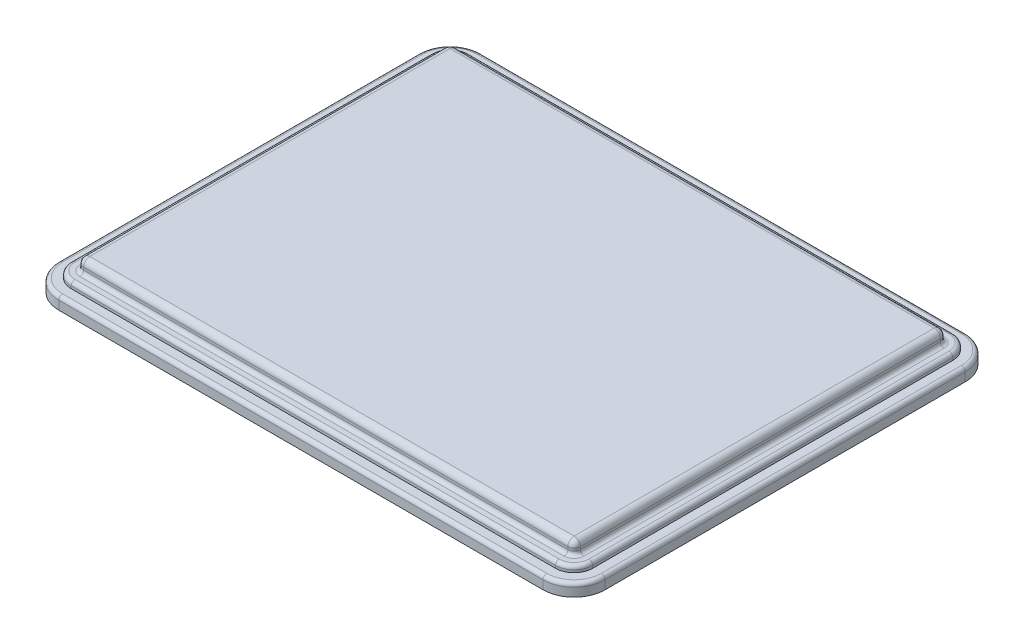
SolidWorks part; units mm, degrees
ref_plane "Front Plane" through (0, 0, 0) normal (0, 0, 1) x (1, 0, 0)
ref_plane "Top Plane" through (0, 0, 0) normal (0, 1, 0) x (1, 0, 0)
ref_plane "Right Plane" through (0, 0, 0) normal (1, 0, 0) x (0, 0, -1)
sketch "Sketch1" plane through (0, 0, 0) normal (0, 1, 0) x (1, 0, 0)
  line L1 (-200, 150) -> (200, 150)
  line L2 (-200, 150) -> (-200, -150)
  line L3 (-200, -150) -> (200, -150)
  line L4 (200, 150) -> (200, -150)
  line L5 (-200, 150) -> (200, -150) construction
  line L6 (-200, -150) -> (200, 150) construction
  point P0 (0, 0)
  dimension "D1" = 400
  dimension "D2" = 300
extrude "Boss-Extrude1" add sketch "Sketch1" along normal blind 10 contours L1 L4 L3 L2
fillet "Fillet1" radius 5 4 edges at (-200, 5, -150) (-200, 5, 150) (200, 5, -150) (200, 5, 150)
fillet "Fillet2" radius 5 8 edges at (198.5355, 10, -148.5355) (200, 10, 0) (198.5355, 10, 148.5355) (0, 10, 150) (-198.5355, 10, 148.5355) (-200, 10, 0) (-198.5355, 10, -148.5355) (0, 10, -150)
sketch "Sketch2" plane through (0, 0, 0) normal (0, -1, 0) x (1, 0, 0)
  line L0 (195, 160) -> (-195, 160)
  line L1 (-210, 145) -> (-210, -145)
  line L2 (-195, -160) -> (195, -160)
  line L3 (210, -145) -> (210, 145)
  line L4 (-200, 145) -> (-200, -145)
  line L5 (-195, -150) -> (195, -150)
  line L6 (200, -145) -> (200, 145)
  line L7 (195, 150) -> (-195, 150)
  line L8 (-200, 145) -> (-200, -145)
  line L9 (-195, -150) -> (195, -150)
  line L10 (200, -145) -> (200, 145)
  line L11 (195, 150) -> (-195, 150)
  arc A0 (-195, 160) -> (-210, 145) centre (-195, 145) ccw
  arc A1 (-210, -145) -> (-195, -160) centre (-195, -145) ccw
  arc A2 (195, -160) -> (210, -145) centre (195, -145) ccw
  arc A3 (210, 145) -> (195, 160) centre (195, 145) ccw
  arc A4 (-200, -145) -> (-195, -150) centre (-195, -145) ccw
  arc A5 (195, -150) -> (200, -145) centre (195, -145) ccw
  arc A6 (200, 145) -> (195, 150) centre (195, 145) ccw
  arc A7 (-195, 150) -> (-200, 145) centre (-195, 145) ccw
  arc A8 (-200, -145) -> (-195, -150) centre (-195, -145) ccw
  arc A9 (195, -150) -> (200, -145) centre (195, -145) ccw
  arc A10 (200, 145) -> (195, 150) centre (195, 145) ccw
  arc A11 (-195, 150) -> (-200, 145) centre (-195, 145) ccw
  dimension "D1" = 0
  dimension "D2" = 10
extrude "Boss-Extrude2" add sketch "Sketch2" along normal blind 5 contours L0 A0 L1 A1 L2 A2 L3 A3
sketch "Sketch3" plane through (0, -5, 0) normal (0, -1, 0) x (1, 0, 0)
  line L0 (195, 170) -> (-195, 170)
  line L1 (-220, 145) -> (-220, -145)
  line L2 (-195, -170) -> (195, -170)
  line L3 (220, -145) -> (220, 145)
  line L4 (195, 160) -> (-195, 160)
  line L5 (-210, 145) -> (-210, -145)
  line L6 (-195, -160) -> (195, -160)
  line L7 (210, -145) -> (210, 145)
  line L8 (195, 160) -> (-195, 160)
  line L9 (-210, 145) -> (-210, -145)
  line L10 (-195, -160) -> (195, -160)
  line L11 (210, -145) -> (210, 145)
  arc A0 (-195, 170) -> (-220, 145) centre (-195, 145) ccw
  arc A1 (-220, -145) -> (-195, -170) centre (-195, -145) ccw
  arc A2 (195, -170) -> (220, -145) centre (195, -145) ccw
  arc A3 (220, 145) -> (195, 170) centre (195, 145) ccw
  arc A4 (210, 145) -> (195, 160) centre (195, 145) ccw
  arc A5 (-195, 160) -> (-210, 145) centre (-195, 145) ccw
  arc A6 (-210, -145) -> (-195, -160) centre (-195, -145) ccw
  arc A7 (195, -160) -> (210, -145) centre (195, -145) ccw
  arc A8 (210, 145) -> (195, 160) centre (195, 145) ccw
  arc A9 (-195, 160) -> (-210, 145) centre (-195, 145) ccw
  arc A10 (-210, -145) -> (-195, -160) centre (-195, -145) ccw
  arc A11 (195, -160) -> (210, -145) centre (195, -145) ccw
  point P4 (0, 0)
  point P24 (-195, 160)
  point P26 (215, 145)
  point P27 (0, 0)
  dimension "D1" = 0
  dimension "D2" = 10
extrude "Boss-Extrude5" add sketch "Sketch3" along normal blind 10 separate body contours L1 A1 L2 A2 L3 A3 L0 A0
fillet "Fillet3" radius 3 16 edges at (-198.5355, 0, 148.5355) (0, 0, 150) (198.5355, 0, 148.5355) (200, 0, 0) (198.5355, 0, -148.5355) (0, 0, -150) (-198.5355, 0, -148.5355) (-200, 0, 0) (0, 0, 160) (-205.6066, 0, 155.6066) (-210, 0, 0) (-205.6066, 0, -155.6066) (0, 0, -160) (205.6066, 0, -155.6066) (210, 0, 0) (205.6066, 0, 155.6066)
fillet "Fillet4" radius 3 8 edges at (-220, -5, 0) (-212.6777, -5, -162.6777) (0, -5, -170) (212.6777, -5, -162.6777) (220, -5, 0) (212.6777, -5, 162.6777) (0, -5, 170) (-212.6777, -5, 162.6777)
